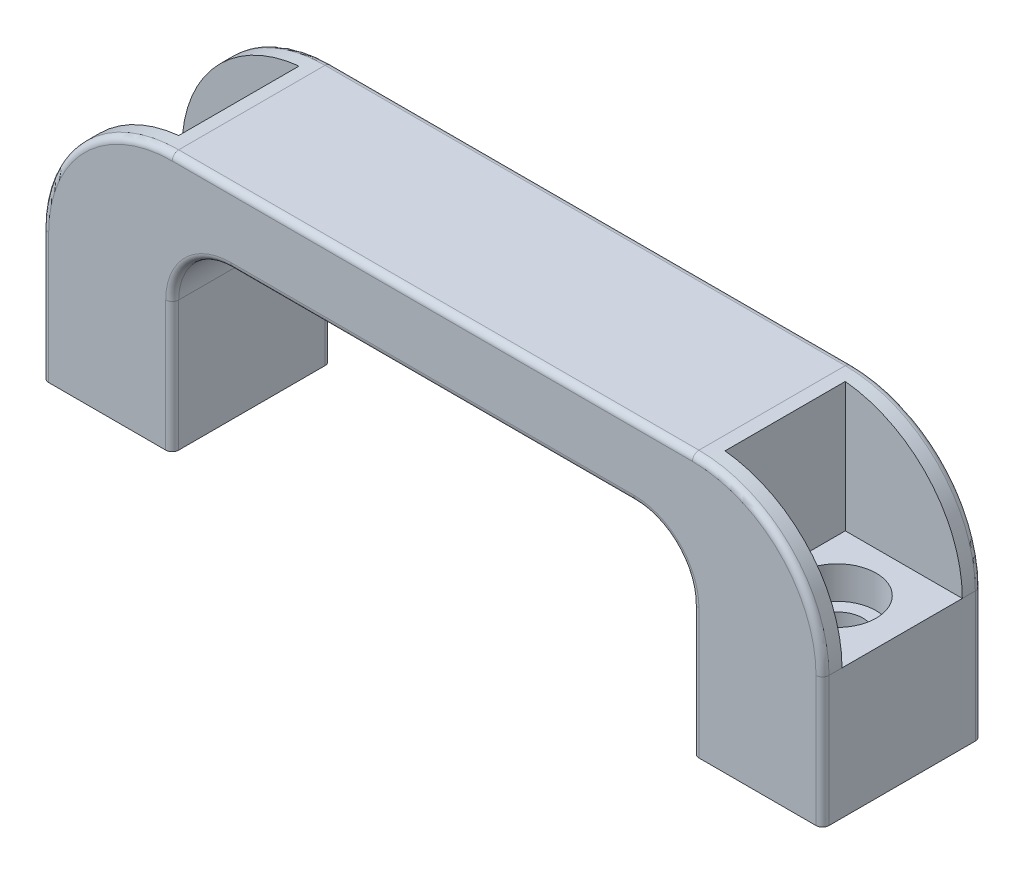
SolidWorks part; units mm, degrees
material "ABS"
ref_plane "Спереди" through (0, 0, 0) normal (0, 0, 1) x (1, 0, 0)
ref_plane "Сверху" through (0, 0, 0) normal (0, 1, 0) x (1, 0, 0)
ref_plane "Справа" through (0, 0, 0) normal (1, 0, 0) x (0, 0, -1)
sketch "Эскиз1" plane through (0, 0, 0) normal (0, 0, 1) x (1, 0, 0)
  line L0 (0, 0) -> (0, 40)
  line L1 (0, 40) -> (120, 40)
  line L2 (120, 40) -> (120, 0)
  line L3 (120, 0) -> (100, 0)
  line L4 (100, 0) -> (100, 29)
  line L5 (100, 29) -> (20, 29)
  line L6 (20, 29) -> (20, 0)
  line L7 (20, 0) -> (0, 0)
  dimension "D1" = 11
  dimension "D2" = 120
  dimension "D3" = 20
  dimension "D4" = 20
  dimension "D5" = 40
extrude "Бобышка-Вытянуть1" add sketch "Эскиз1" along normal blind 24.5
fillet "Скругление1" radius 20 2 edges at (0, 40, 12.25) (120, 40, 12.25)
fillet "Скругление2" radius 9 2 edges at (20, 29, 12.25) (100, 29, 12.25)
sketch "Эскиз2" plane through (120, 0, 0) normal (1, 0, 0) x (0, 0, -1)
  line L0 (0, 20) -> (-24.5, 20) construction
  line L1 (-21.5, 20) -> (-3, 20)
  line L2 (-21.5, 20) -> (-21.5, 46.0601)
  line L3 (-21.5, 46.0601) -> (-3, 46.0601)
  line L4 (-3, 20) -> (-3, 46.0601)
  line L5 (-24.5, 40) -> (-24.5, 20) construction
  line L6 (0, 20) -> (0, 40) construction
  dimension "D1" = 3
  dimension "D2" = 3
extrude "Вырез-Вытянуть1" cut sketch "Эскиз2" against normal blind 18
sketch "Эскиз3" plane through (0, 0, 0) normal (-1, 0, 0) x (0, 0, 1)
  line L0 (24.5, 20) -> (0, 20) construction
  line L1 (3, 20) -> (21.5, 20)
  line L2 (3, 20) -> (3, 41.4871)
  line L3 (3, 41.4871) -> (21.5, 41.4871)
  line L4 (21.5, 20) -> (21.5, 41.4871)
  line L5 (0, 40) -> (0, 20) construction
  line L6 (24.5, 20) -> (24.5, 40) construction
  dimension "D1" = 3
  dimension "D2" = 3
extrude "Вырез-Вытянуть2" cut sketch "Эскиз3" against normal blind 18
fillet "Скругление3" radius 1 20 edges at (20, 10, 24.5) (22.636, 26.364, 24.5) (60, 29, 24.5) (97.364, 26.364, 24.5) (20, 10, 0) (22.636, 26.364, 0) (60, 29, 0) (97.364, 26.364, 0) (120, 10, 24.5) (114.1421, 34.1421, 24.5) (0, 10, 24.5) (5.8579, 34.1421, 24.5) (120, 10, 0) (114.1421, 34.1421, 0) (0, 10, 0) (5.8579, 34.1421, 0) (100, 10, 24.5) (100, 10, 0) (60, 40, 24.5) (60, 40, 0)
sketch "Эскиз6" plane through (0, 0, 0) normal (0, -1, 0) x (-1, 0, 0)
  line L0 (-1, -24.5) -> (-19, -24.5) construction
  line L1 (0, -23.5) -> (0, -1) construction
  line L2 (-101, -24.5) -> (-119, -24.5) construction
  line L4 (-120, -23.5) -> (-120, -1) construction
  circle A0 centre (-10, -12.25) radius 4
  circle A1 centre (-110, -12.25) radius 4
  dimension "D1" = 12.25
  dimension "D2" = 8
  dimension "D3" = 10
  dimension "D4" = 8
  dimension "D5" = 12.25
  dimension "D6" = 10
extrude "Вырез-Вытянуть3" cut sketch "Эскиз6" against normal through all
sketch "Эскиз7" plane through (0, 20, 0) normal (0, 1, 0) x (1, 0, 0)
  circle A0 centre (10, -12.25) radius 6
  circle A1 centre (110, -12.25) radius 6
  dimension "D1" = 12
  dimension "D2" = 12
extrude "Вырез-Вытянуть4" cut sketch "Эскиз7" against normal blind 5
ref_plane "Плоскость1" through (0, 0, 12.25) normal (0, 0, -1) x (-1, 0, 0)
ref_plane "Плоскость2" through (60, 0, 0) normal (1, 0, 0) x (0, 0, -1)
